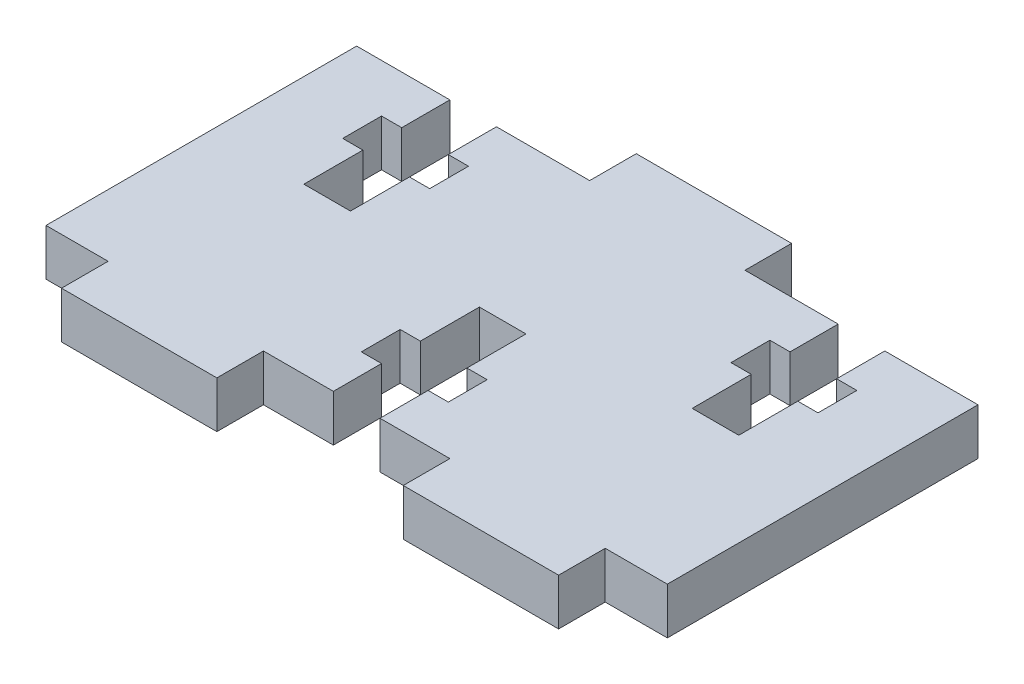
SolidWorks part; units mm, degrees
ref_plane "Front Plane" through (0, 0, 0) normal (0, 0, 1) x (1, 0, 0)
ref_plane "Top Plane" through (0, 0, 0) normal (0, 1, 0) x (1, 0, 0)
ref_plane "Right Plane" through (0, 0, 0) normal (1, 0, 0) x (0, 0, -1)
sketch "Sketch2" plane through (0, 0, 0) normal (0, 1, 0) x (1, 0, 0)
  line L0 (-20, 10) -> (-20, 9.4) construction
  line L1 (0, 0) -> (-4, 0)
  line L2 (0, 0) -> (0, 20)
  line L3 (0, 20) -> (-6, 20)
  line L4 (-40, 0) -> (-40, 20)
  line L5 (0, 10) -> (-40, 10) construction
  line L6 (-4, 0) -> (-4, -3)
  line L7 (-4, -3) -> (-14, -3)
  line L8 (-14, -3) -> (-14, 0)
  line L9 (-14, 0) -> (-18.5, 0)
  line L10 (-18.5, 0) -> (-18.5, 3.1)
  line L11 (-18.5, 3.1) -> (-17.2, 3.1)
  line L12 (-17.2, 3.1) -> (-17.2, 5.6)
  line L13 (-17.2, 5.6) -> (-18.5, 5.6)
  line L14 (-18.5, 5.6) -> (-18.5, 9.4)
  line L15 (-18.5, 9.4) -> (-21.5, 9.4)
  line L16 (-21.5, 9.4) -> (-21.5, 5.6)
  line L17 (-21.5, 5.6) -> (-22.8, 5.6)
  line L18 (-22.8, 5.6) -> (-22.8, 3.1)
  line L19 (-22.8, 3.1) -> (-21.5, 3.1)
  line L20 (-21.5, 3.1) -> (-21.5, 0)
  line L21 (-21.5, 0) -> (-26, 0)
  line L22 (-26, -3) -> (-26, 0)
  line L23 (-36, -3) -> (-26, -3)
  line L24 (-36, 0) -> (-36, -3)
  line L25 (-36, 0) -> (-40, 0)
  line L26 (-6, 20) -> (-6, 16.9)
  line L27 (-15, 20) -> (-15, 23)
  line L28 (-15, 23) -> (-25, 23)
  line L29 (-25, 23) -> (-25, 20)
  line L30 (-25, 20) -> (-31, 20)
  line L31 (-6, 16.9) -> (-4.7, 16.9)
  line L32 (-4.7, 16.9) -> (-4.7, 14.4)
  line L33 (-4.7, 14.4) -> (-6, 14.4)
  line L34 (-6, 14.4) -> (-6, 10.6)
  line L35 (-6, 10.6) -> (-9, 10.6)
  line L36 (-9, 10.6) -> (-9, 14.4)
  line L37 (-9, 14.4) -> (-10.3, 14.4)
  line L38 (-10.3, 14.4) -> (-10.3, 16.9)
  line L39 (-10.3, 16.9) -> (-9, 16.9)
  line L40 (-9, 16.9) -> (-9, 20)
  line L41 (-9, 20) -> (-15, 20)
  line L42 (-31, 16.9) -> (-31, 20)
  line L43 (-29.7, 16.9) -> (-31, 16.9)
  line L44 (-29.7, 14.4) -> (-29.7, 16.9)
  line L45 (-31, 14.4) -> (-29.7, 14.4)
  line L46 (-31, 10.6) -> (-31, 14.4)
  line L47 (-34, 10.6) -> (-31, 10.6)
  line L48 (-34, 14.4) -> (-34, 10.6)
  line L49 (-35.3, 14.4) -> (-34, 14.4)
  line L50 (-34, 16.9) -> (-35.3, 16.9)
  line L51 (-35.3, 16.9) -> (-35.3, 14.4)
  line L52 (-34, 20) -> (-34, 16.9)
  line L53 (-34, 20) -> (-40, 20)
  point P5 (-4, 0)
  point P6 (-6, 20)
  point P48 (-5.35, 16.9)
  point P49 (-9.65, 16.9)
  point P52 (-30.35, 16.9)
  point P60 (-34.65, 16.9)
  dimension "D1" = 40
  dimension "D2" = 20
  dimension "D3" = 4
  dimension "D4" = 10
  dimension "D5" = 3.1
  dimension "D6" = 2.5
  dimension "D7" = 3.8
  dimension "D8" = 3
  dimension "D9" = 1.3
  dimension "D10" = 3
  dimension "D11" = 4.5
  dimension "D12" = 6
  dimension "D13" = 6
extrude "Boss-Extrude2" add sketch "Sketch2" along normal blind 3
